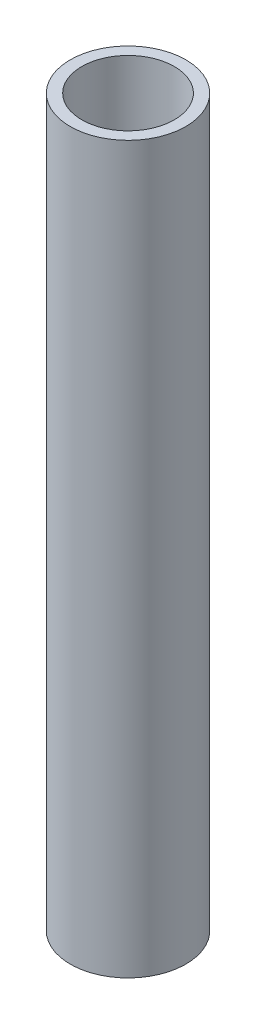
SolidWorks part; units mm, degrees
ref_plane "Front Plane" through (0, 0, 0) normal (0, 0, 1) x (1, 0, 0)
ref_plane "Top Plane" through (0, 0, 0) normal (0, 1, 0) x (1, 0, 0)
ref_plane "Right Plane" through (0, 0, 0) normal (1, 0, 0) x (0, 0, -1)
sketch "Sketch1" plane through (0, 0, 0) normal (0, 1, 0) x (1, 0, 0)
  circle A0 centre (0, 0) radius 15
  circle A1 centre (0, 0) radius 12
  dimension "D1" = 30
  dimension "D2" = 24
extrude "Boss-Extrude1" add sketch "Sketch1" along normal blind 188.23
